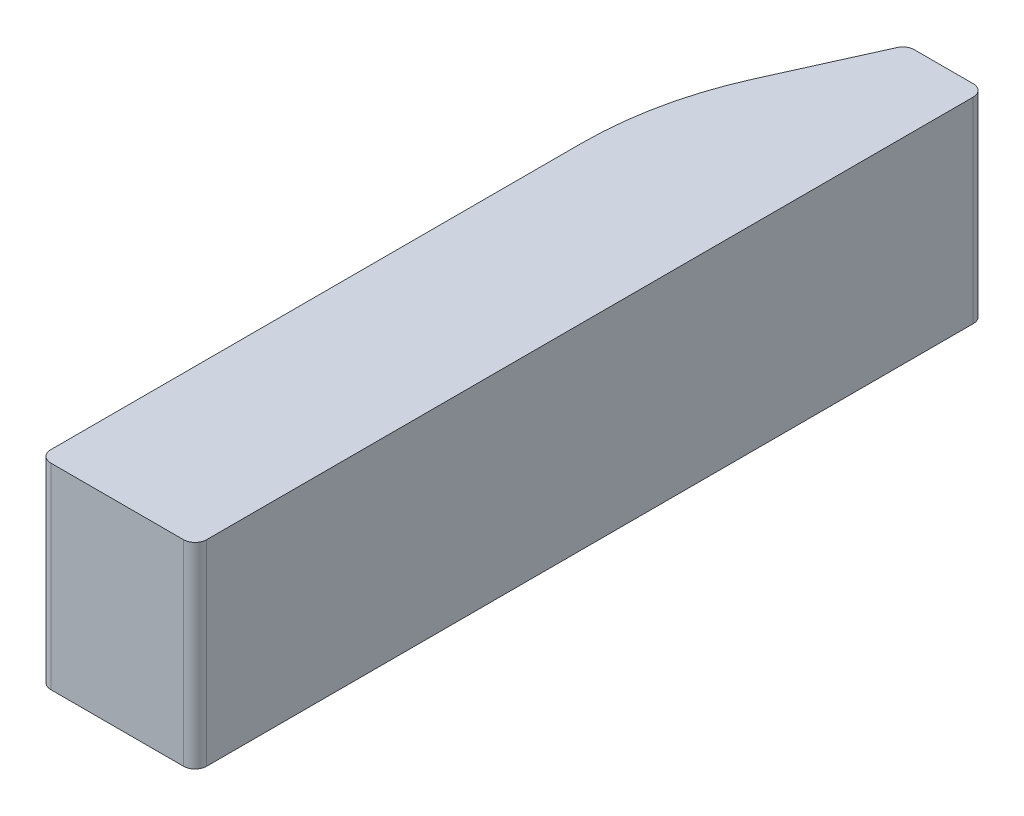
SolidWorks part; units mm, degrees
material "3DP"
ref_plane "正面" through (0, 0, 0) normal (0, 0, 1) x (1, 0, 0)
ref_plane "平面" through (0, 0, 0) normal (0, 1, 0) x (1, 0, 0)
ref_plane "右側面" through (0, 0, 0) normal (1, 0, 0) x (0, 0, -1)
sketch "ｽｹｯﾁ1" plane through (0, 0, 0) normal (0, 1, 0) x (1, 0, 0)
  line L1 (0, 0) -> (13.5, 0)
  line L2 (0, 0) -> (0, 68.4)
  line L3 (0, 68.4) -> (13.5, 68.4)
  line L4 (13.5, 0) -> (13.5, 68.4)
  dimension "D1" = 13.5
  dimension "D2" = 68.4
extrude "ﾎﾞｽ - 押し出し1" add sketch "ｽｹｯﾁ1" along normal blind 17
sketch "ｽｹｯﾁ2" plane through (0, 0, 0) normal (0, -1, 0) x (1, 0, 0)
  line L0 (8.5, 0) -> (8.5, -68.4) construction
  line L1 (0, 0) -> (13.5, 0) construction
  line L3 (13.5, -34.2) -> (0, -34.2) construction
  line L4 (13.5, 0) -> (13.5, -68.4) construction
  line L5 (0, -68.4) -> (0, 0) construction
  circle A0 centre (8.5, -47.4) radius 2.75
  circle A1 centre (8.5, -11) radius 2.75
  point P16 (0, 0)
  point P17 (0, 0)
  dimension "D1" = 5.5
  dimension "D2" = 36.4
  dimension "D3" = 11
  dimension "D4" = 5
extrude "ｶｯﾄ - 押し出し1" cut sketch "ｽｹｯﾁ2" against normal blind 5
sketch "ｽｹｯﾁ3" plane through (0, 17, 0) normal (0, 1, 0) x (1, 0, 0)
  line L0 (6.75, 68.4) -> (0, 68.4)
  line L1 (13.5, 68.4) -> (0, 68.4) construction
  line L2 (0, 68.4) -> (0, 53.4)
  line L3 (0, 68.4) -> (0, 0) construction
  line L4 (0, 53.4) -> (6.75, 68.4)
  dimension "D1" = 15
extrude "ｶｯﾄ - 押し出し2" cut sketch "ｽｹｯﾁ3" against normal up to surface (17 mm away) up to face at (8.5, 0, -50.15)
sketch "ｽｹｯﾁ4" plane through (0, 0, 0) normal (0, -1, 0) x (1, 0, 0)
  line L0 (0, -47) -> (-4, -37)
  line L1 (0, -53.4) -> (0, 0) construction
  line L2 (-4, -37) -> (-4, -27)
  line L3 (-4, -27) -> (0, -27)
  line L4 (0, -27) -> (0, -47)
  line L5 (0, 0) -> (13.5, 0) construction
  dimension "D1" = 4
  dimension "D2" = 20
  dimension "D3" = 10
  dimension "D4" = 27
extrude "ﾎﾞｽ - 押し出し2" add sketch "ｽｹｯﾁ4" against normal blind 5.5
fillet "ﾌｨﾚｯﾄ1" radius 30 1 edges at (0, 8.5, -53.4)
fillet "ﾌｨﾚｯﾄ2" radius 1 4 edges at (0, 8.5, 0) (13.5, 8.5, 0) (13.5, 8.5, -68.4) (6.75, 8.5, -68.4)
sketch "ｽｹｯﾁ8" plane through (0, 17, 0) normal (0, 1, 0) x (1, 0, 0)
  line L0 (0, 46.961) -> (0, 27) construction
  line L1 (0, 46.961) -> (-4, 46.961)
  line L2 (0, 46.961) -> (0, 27)
  line L3 (0, 27) -> (-4, 27)
  line L4 (-4, 46.961) -> (-4, 27)
  arc A0 (2.6424, 59.2719) -> (0, 46.961) centre (30, 46.961) ccw construction
extrude "ｶｯﾄ - 押し出し5" cut sketch "ｽｹｯﾁ8" against normal up to surface (17 mm away) up to face at (4.6919, 0, -36.2577)
